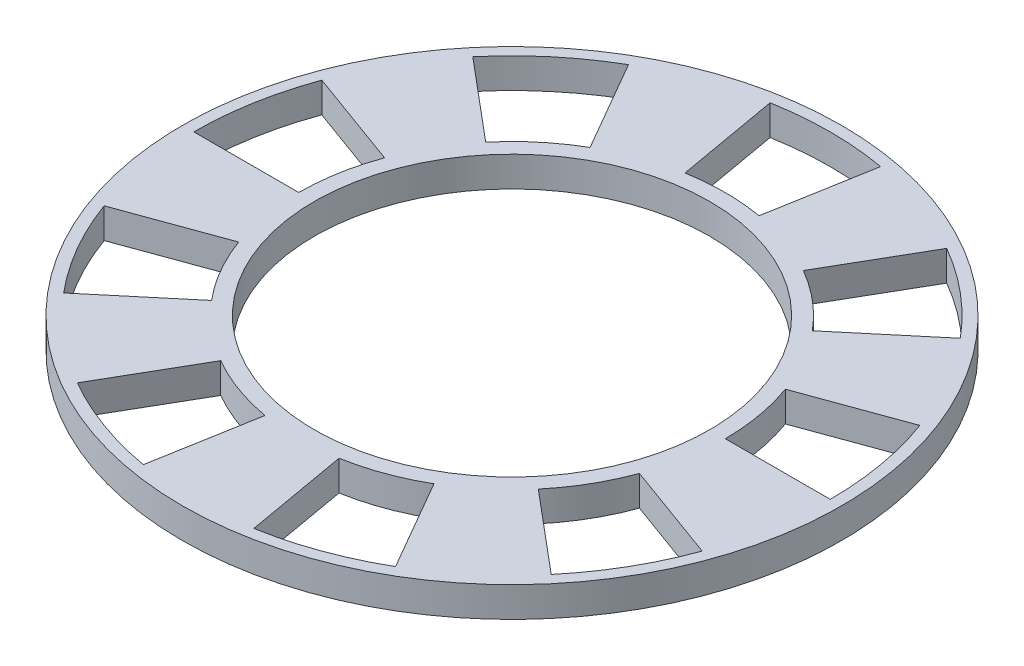
SolidWorks part; units mm, degrees
ref_plane "Front Plane" through (0, 0, 0) normal (0, 0, 1) x (1, 0, 0)
ref_plane "Top Plane" through (0, 0, 0) normal (0, 1, 0) x (1, 0, 0)
ref_plane "Right Plane" through (0, 0, 0) normal (1, 0, 0) x (0, 0, -1)
sketch "Sketch1" plane through (0, 0, 0) normal (0, 1, 0) x (1, 0, 0)
  circle A0 centre (0, 0) radius 44.45
  circle A1 centre (0, 0) radius 26.67
  dimension "D1" = 17.78
  dimension "D2" = 53.34
extrude "Boss-Extrude1" add sketch "Sketch1" along normal blind 4.064
sketch "Sketch2" plane through (0, 4.064, 0) normal (0, 1, 0) x (1, 0, 0)
  line L0 (-28.7608, 0) -> (-42.9222, 0)
  line L1 (-27.0264, 9.8368) -> (-40.3337, 14.6802)
  circle A0 centre (0, 0) radius 26.67 construction
  arc A1 (-27.0264, 9.8368) -> (-28.7608, 0) centre (0, 0) ccw
  arc A2 (-40.3337, 14.6802) -> (-42.9222, 0) centre (0, 0) ccw
  dimension "D1" = 28.7608
  dimension "D2" = 14.1613
  dimension "D3" = 20
extrude "Cut-Extrude1" cut sketch "Sketch2" against normal up to next
pattern_circular "CirPattern1" count 9 over 360 about axis through (0, 0, 0) along (0, 1, 0) of "Cut-Extrude1"
sketch "Sketch3" plane through (0, 4.064, 0) normal (0, 1, 0) x (1, 0, 0)
  line L0 (-38.4948, 22.225) -> (0, 0) construction
  line L1 (-27.0264, 9.8368) -> (-40.3337, 14.6802) construction
  circle A0 centre (0, 0) radius 44.45 construction
  dimension "D1" = 10
